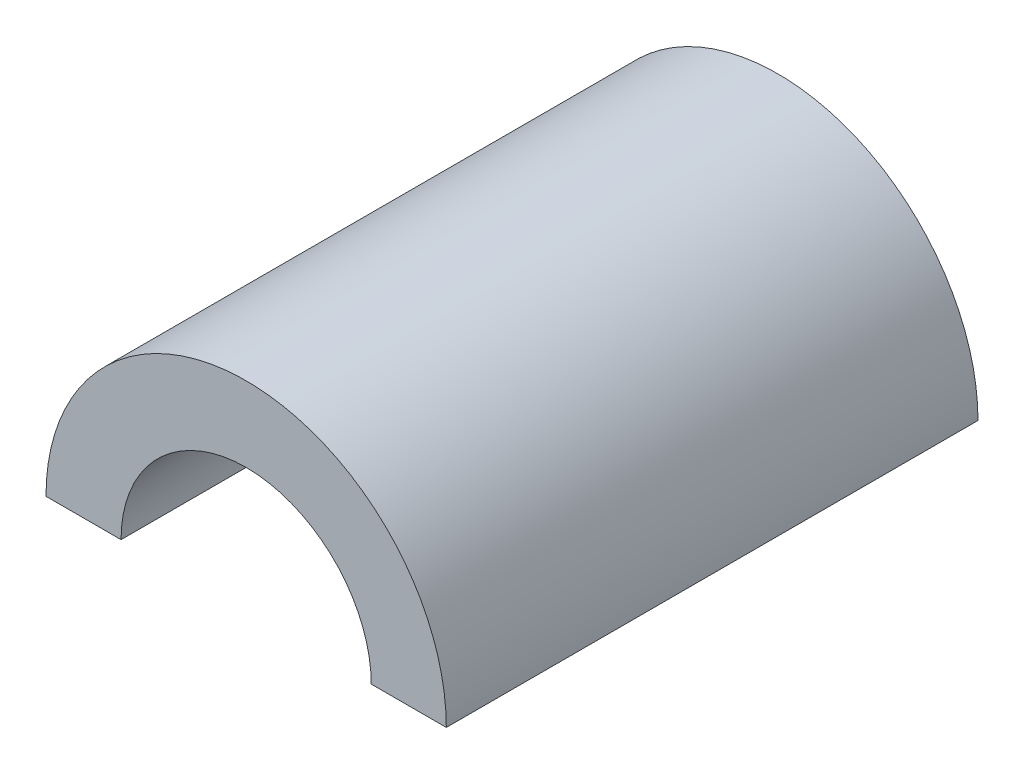
SolidWorks part; units mm, degrees
ref_plane "Front Plane" through (0, 0, 0) normal (0, 0, 1) x (1, 0, 0)
ref_plane "Top Plane" through (0, 0, 0) normal (0, 1, 0) x (1, 0, 0)
ref_plane "Right Plane" through (0, 0, 0) normal (1, 0, 0) x (0, 0, -1)
sketch "Sketch1" plane through (0, 0, 0) normal (0, 0, 1) x (1, 0, 0)
  arc A0 (0, 0) -> (64, 0) centre (32, 0) cw
  point P3 (0, 0)
  point P5 (0, 0)
  point P6 (0, 0)
extrude "Extrude-Thin2" add sketch "Sketch1" against normal blind 85 thin
